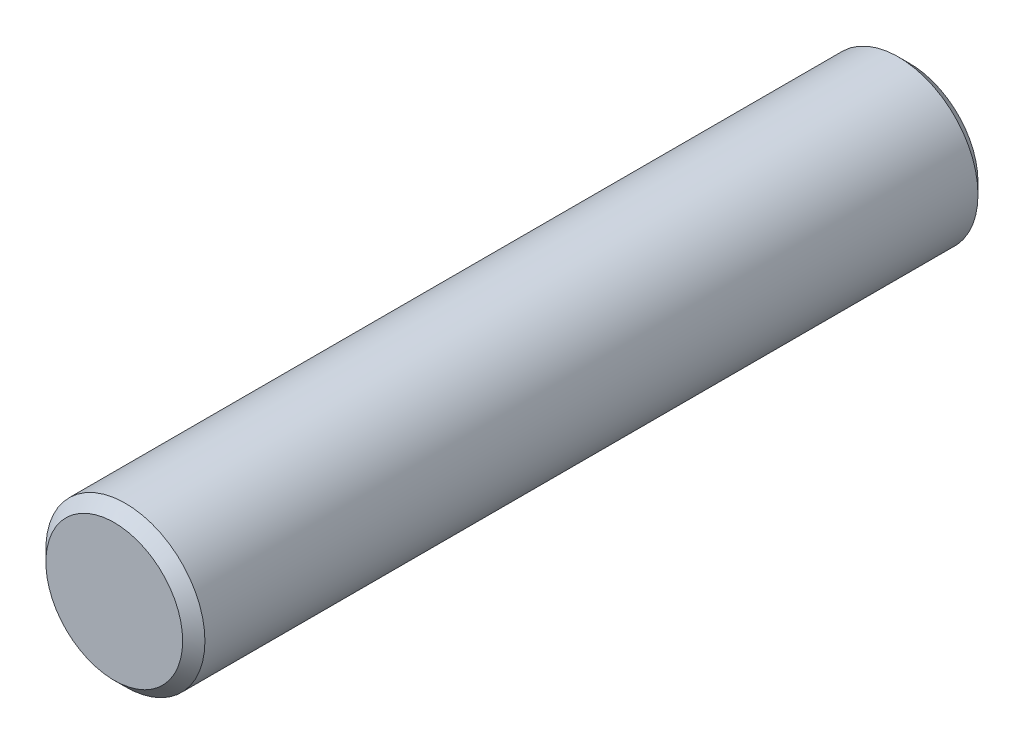
SolidWorks part; units mm, degrees
ref_plane "Přední rovina" through (0, 0, 0) normal (0, 0, 1) x (1, 0, 0)
ref_plane "Vrchní rovina" through (0, 0, 0) normal (0, 1, 0) x (1, 0, 0)
ref_plane "Pravá rovina" through (0, 0, 0) normal (1, 0, 0) x (0, 0, -1)
sketch "Skica1" plane through (0, 0, 0) normal (0, 0, 1) x (1, 0, 0)
  circle A0 centre (0, 0) radius 1.5
  dimension "M" = 3
extrude "Vysunout1" add sketch "Skica1" along normal blind 15
cosmetic thread "Kosmetický závit1" parameters "b"=12, "D2"=2.55
cosmetic thread "Kosmetický závit3" parameters "e"=3, "D2"=2.55
chamfer "Zkosit1" distance 0.21 angle 45 2 edges at (1.5, 0, 0) (1.5, 0, 15)
equation "\"D1@Zkosit1\" = \"M@Skica1\" * 0.07"
equation "\"D2@Kosmetický závit3\" = 0.85*\"M@Skica1\""
equation "\"D2@Kosmetický závit1\" = 0.85*\"M@Skica1\""
